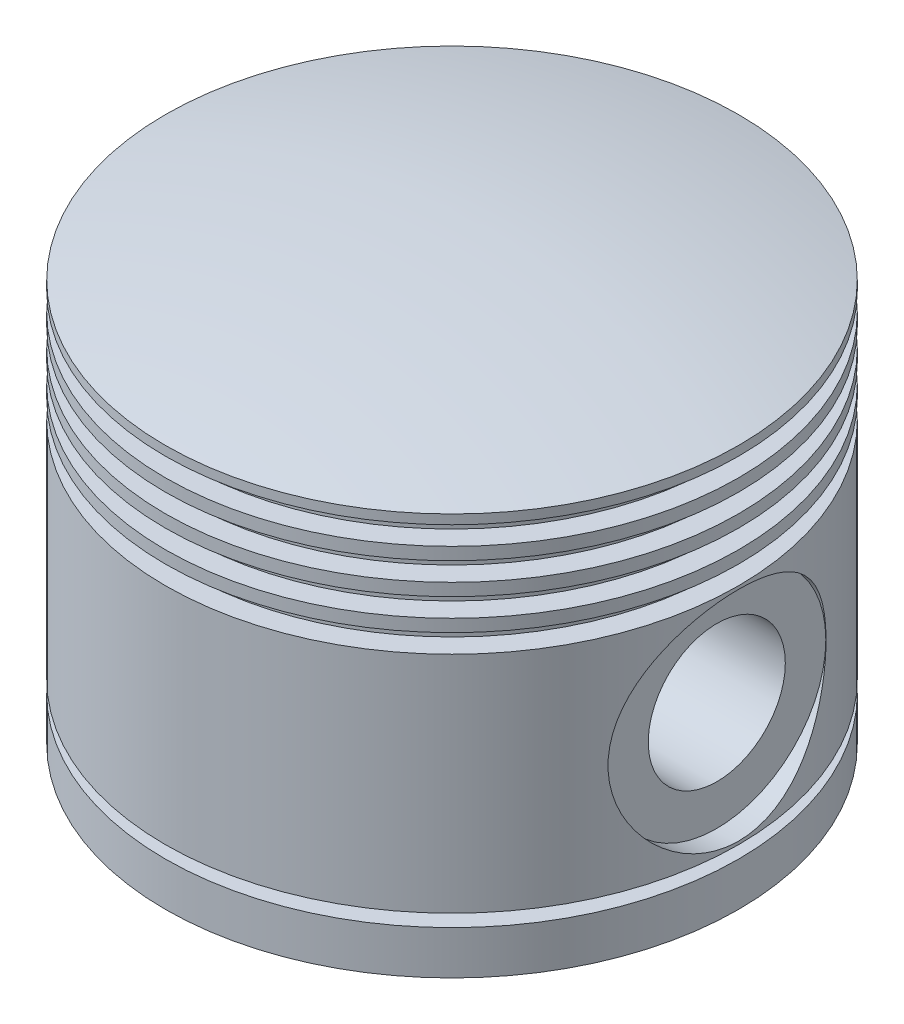
SolidWorks part; units mm, degrees
ref_plane "Front Plane" through (0, 0, 0) normal (0, 0, 1) x (1, 0, 0)
ref_plane "Top Plane" through (0, 0, 0) normal (0, 1, 0) x (1, 0, 0)
ref_plane "Right Plane" through (0, 0, 0) normal (1, 0, 0) x (0, 0, -1)
sketch "Sketch1" plane through (0, 0, 0) normal (0, 0, 1) x (1, 0, 0)
  line L0 (0, 41.4753) -> (0, -28.7047) construction
  line L1 (-46, -28.7047) -> (39.7274, -28.7047) construction
  line L2 (-46, 35.7953) -> (-46, 34.2953)
  line L3 (-46, 34.2953) -> (-42.6045, 34.2953)
  line L4 (-42.6045, 34.2953) -> (-42.6045, 31.2953)
  line L5 (-42.6045, 31.2953) -> (-46, 31.2953)
  line L6 (-46, 31.2953) -> (-46, 29.2953)
  line L7 (-46, 29.2953) -> (-42.6045, 29.2953)
  line L8 (-42.6045, 29.2953) -> (-42.6045, 26.2953)
  line L9 (-42.6045, 26.2953) -> (-46, 26.2953)
  line L10 (-46, 26.2953) -> (-46, 24.2953)
  line L11 (-46, 24.2953) -> (-42.6045, 24.2953)
  line L12 (-42.6045, 24.2953) -> (-42.6045, 21.2953)
  line L13 (-42.6045, 21.2953) -> (-46, 21.2953)
  line L14 (-46, 21.2953) -> (-46, 19.2953)
  line L15 (-46, 19.2953) -> (-42.6045, 19.2953)
  line L16 (-42.6045, 19.2953) -> (-42.6045, 16.2953)
  line L17 (-42.6045, 16.2953) -> (-46, 16.2953)
  line L18 (-46, 16.2953) -> (-46, -19.7047)
  line L19 (-46, -21.7047) -> (-42.5, -21.7047)
  line L20 (-42.5, -21.7047) -> (-42.5, -19.7047)
  line L21 (-42.5, -19.7047) -> (-46, -19.7047)
  line L22 (-46, -21.7047) -> (-46, -28.7047)
  line L23 (0, 41.4753) -> (0, 33.2953)
  line L24 (0, 33.2953) -> (-37, 33.2953)
  line L25 (-37, 33.2953) -> (-37, -28.7047)
  line L26 (-37, -28.7047) -> (-46, -28.7047)
  arc A0 (0, 41.4753) -> (-46, 35.7953) centre (-0.0133, -147.5247) ccw
  dimension "D3" = 1.5
  dimension "D11" = 189
  dimension "D1" = 46
  dimension "D2" = 70.18
  dimension "D4" = 3
  dimension "D5" = 2
  dimension "D6" = 7
  dimension "D7" = 2
  dimension "D8" = 2
  dimension "D9" = 2
  dimension "D10" = 45
  dimension "D12" = 42.5
  dimension "D13" = 62
  dimension "D14" = 37
revolve "Revolve1" add sketch "Sketch1" angle 360 about L0
ref_plane "Plane1" through (10, 0, 0) normal (1, 0, 0) x (0, 0, -1)
sketch "Sketch2" plane through (10, 0, 0) normal (1, 0, 0) x (0, 0, -1)
  line L0 (-46, -28.7047) -> (46, -28.7047) construction
  circle A0 centre (0, -1.7047) radius 11
  dimension "D1" = 22
  dimension "D2" = 27
extrude "Cut-Extrude1" cut sketch "Sketch2" against normal through all both and the other way through all
ref_plane "Plane2" through (0, 0, 0) normal (1, 0, 0) x (0, 0, -1)
sketch "Sketch4" plane through (0, 0, 0) normal (1, 0, 0) x (0, 0, -1)
  circle A2 centre (0, -1.7047) radius 17.5
  dimension "D1" = 35
extrude "Cut-Extrude2" cut sketch "Sketch4" against normal blind 3.5 from offset 46
mirror "Mirror1" about plane through (0, 0, 0) normal (1, 0, 0) of "Cut-Extrude2"
sketch "Sketch5" plane through (0, 0, 0) normal (1, 0, 0) x (0, 0, -1)
  circle A0 centre (0, -1.7047) radius 18
  circle A1 centre (0, -1.7047) radius 11
  dimension "D1" = 36
  dimension "D2" = 22
extrude "Boss-Extrude5" add sketch "Sketch5" against normal up to surface (7.3265 mm away) from offset 25 offset against normal yes
mirror "Mirror2" about plane through (0, 0, 0) normal (1, 0, 0) of "Boss-Extrude5"
